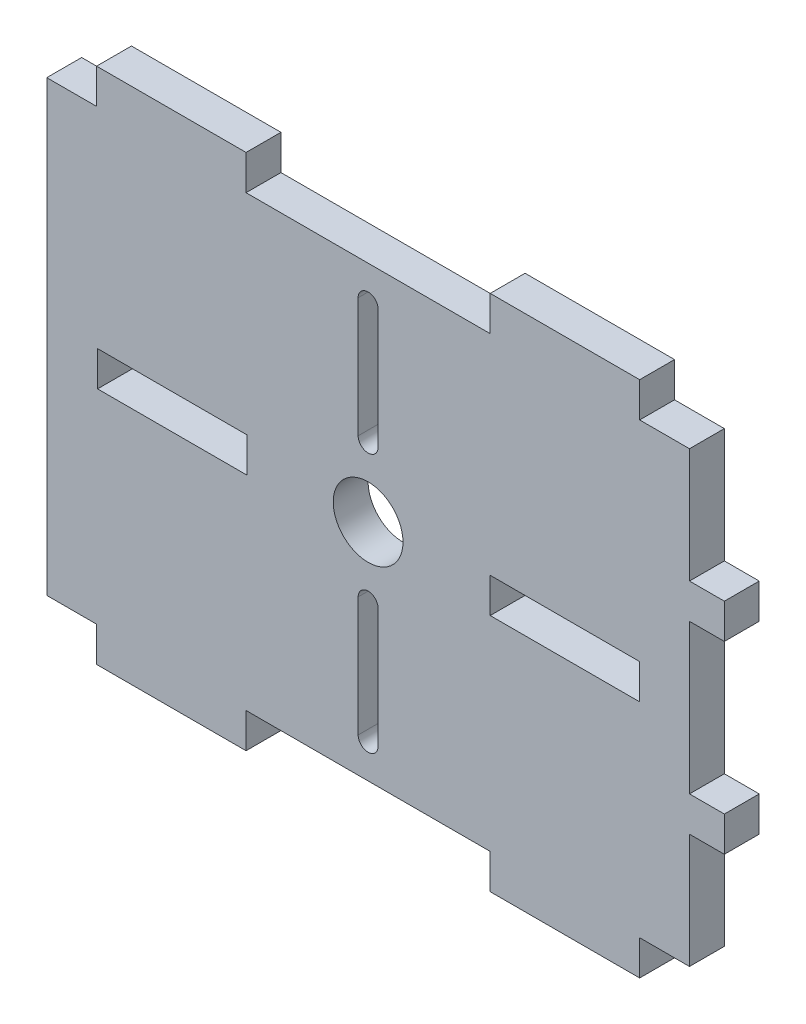
SolidWorks part; units mm, degrees
material "Balsa"
ref_plane "Front Plane" through (0, 0, 0) normal (0, 0, 1) x (1, 0, 0)
ref_plane "Top Plane" through (0, 0, 0) normal (0, 1, 0) x (1, 0, 0)
ref_plane "Right Plane" through (0, 0, 0) normal (1, 0, 0) x (0, 0, -1)
sketch "Sketch1" plane through (0, 0, 0) normal (0, 0, 1) x (1, 0, 0)
  line L0 (27.25, -26) -> (27.25, -22.5)
  line L1 (-32.25, -26) -> (32.25, -26) construction
  line L2 (-32.25, -26) -> (-32.25, 26) construction
  line L3 (-32.25, 26) -> (32.25, 26) construction
  line L4 (32.25, -26) -> (32.25, 26) construction
  line L5 (0, 26) -> (0, -26) construction
  line L6 (-32.25, 0) -> (32.25, 0) construction
  line L7 (27.25, -22.5) -> (32.25, -22.5)
  line L8 (-27.25, -26) -> (-27.25, -22.5)
  line L9 (-27.25, -22.5) -> (-32.25, -22.5)
  line L10 (27.25, 22.5) -> (32.25, 22.5)
  line L11 (27.25, 26) -> (27.25, 22.5)
  line L12 (-27.25, 26) -> (-27.25, 22.5)
  line L13 (-27.25, 22.5) -> (-32.25, 22.5)
  line L14 (12.25, -22.5) -> (-12.25, -22.5)
  line L15 (12.25, -22.5) -> (12.25, -26)
  line L16 (-12.25, -22.5) -> (-12.25, -26)
  line L17 (12.25, 22.5) -> (12.25, 26)
  line L18 (12.25, 22.5) -> (-12.25, 22.5)
  line L19 (-12.25, 22.5) -> (-12.25, 26)
  line L20 (-12.25, -26) -> (-27.25, -26)
  line L21 (-32.25, -22.5) -> (-32.25, 22.5)
  line L22 (-27.25, 26) -> (-12.25, 26)
  line L23 (12.25, 26) -> (27.25, 26)
  line L24 (32.25, 22.5) -> (32.25, 11)
  line L25 (27.25, -26) -> (12.25, -26)
  line L26 (32.25, 11) -> (35.75, 11)
  line L27 (35.75, 11) -> (35.75, 7.5)
  line L28 (35.75, 7.5) -> (32.25, 7.5)
  line L29 (35.75, -7.5) -> (32.25, -7.5)
  line L30 (35.75, -11) -> (35.75, -7.5)
  line L31 (32.25, -11) -> (35.75, -11)
  line L32 (32.25, 7.5) -> (32.25, -7.5)
  line L33 (32.25, -11) -> (32.25, -22.5)
  line L34 (0, 19) -> (0, 7) construction
  line L37 (0, -19) -> (0, -7) construction
  line L40 (1, 19) -> (1, 7)
  line L41 (-1, 19) -> (-1, 7)
  line L42 (1, -19) -> (1, -7)
  line L43 (-1, -19) -> (-1, -7)
  circle A2 centre (0, 0) radius 3.5
  arc A7 (1, 19) -> (-1, 19) centre (0, 19) ccw
  arc A8 (-1, 7) -> (1, 7) centre (0, 7) ccw
  arc A9 (1, -19) -> (-1, -19) centre (0, -19) cw
  arc A10 (-1, -7) -> (1, -7) centre (0, -7) cw
  point P0 (0, 0)
  point P36 (0, -22.5)
  point P39 (0, 13)
  point P44 (0, -13)
  dimension "D6" = 7
  dimension "D11" = 1
  dimension "D1" = 64.5
  dimension "D2" = 52
  dimension "D3" = 3.5
  dimension "D4" = 5
  dimension "D5" = 15
  dimension "D7" = 3.5
  dimension "D8" = 3.5
  dimension "D9" = 15
  dimension "D10" = 12
  dimension "D12" = 13
extrude "Boss-Extrude1" add sketch "Sketch1" along normal blind 3.5
sketch "Sketch2" plane through (0, 0, 0) normal (0, 0, -1) x (-1, 0, 0)
  line L0 (-12.25, 22.5) -> (12.25, 22.5) construction
  line L1 (32.25, 1.5) -> (-35.75, 1.5) construction
  line L2 (32.25, 1.5) -> (32.25, -2) construction
  line L3 (32.25, -2) -> (-35.75, -2) construction
  line L4 (-35.75, 1.5) -> (-35.75, -2) construction
  line L5 (-35.75, 7.5) -> (-35.75, 11) construction
  line L6 (32.25, 22.5) -> (32.25, -22.5) construction
  line L7 (-32.25, -7.5) -> (-32.25, 7.5) construction
  line L8 (27.15, -2) -> (12.15, -2)
  line L9 (27.15, -2) -> (27.15, 1.5)
  line L10 (27.15, 1.5) -> (12.15, 1.5)
  line L11 (12.15, -2) -> (12.15, 1.5)
  line L12 (-27.25, 1.5) -> (-12.25, 1.5)
  line L13 (-27.25, 1.5) -> (-27.25, -2)
  line L14 (-27.25, -2) -> (-12.25, -2)
  line L15 (-12.25, 1.5) -> (-12.25, -2)
  dimension "D1" = 21
  dimension "D2" = 3.5
  dimension "D3" = 15
  dimension "D4" = 5
  dimension "D5" = 5.1
extrude "Cut-Extrude1" cut sketch "Sketch2" against normal through all
